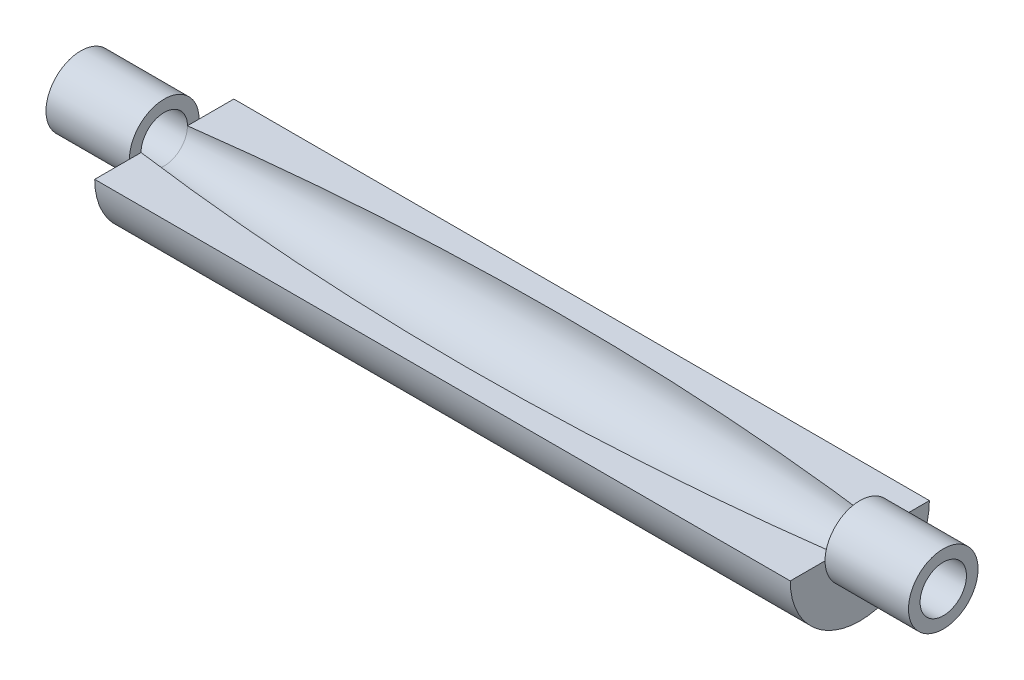
SolidWorks part; units mm, degrees
ref_plane "Front Plane" through (0, 0, 0) normal (0, 0, 1) x (1, 0, 0)
ref_plane "Top Plane" through (0, 0, 0) normal (0, 1, 0) x (1, 0, 0)
ref_plane "Right Plane" through (0, 0, 0) normal (1, 0, 0) x (0, 0, -1)
sketch "Sketch2" plane through (0, 0, 0) normal (0, 1, 0) x (1, 0, 0)
  line L0 (-186, -15) -> (-150, -15)
  line L1 (-150, -15) -> (-150, -30)
  line L2 (-150, -30) -> (150, -30)
  line L3 (150, -30) -> (150, -15)
  line L4 (150, -15) -> (186, -15)
  line L5 (186, -15) -> (186, -10)
  line L6 (186, -10) -> (150, -10)
  line L9 (-150, -10) -> (-186, -10)
  line L10 (-186, -10) -> (-186, -15)
  line L11 (-186, 0) -> (186, 0) construction
  arc A0 (-150, -10) -> (150, -10) centre (0, 1110) ccw
  point P16 (0, 0)
  point P17 (0, -20)
  dimension "D1" = 300
  dimension "D2" = 5
  dimension "D3" = 36
  dimension "D4" = 20
  dimension "D5" = 10
  dimension "D6" = 10
revolve "Revolve2" add sketch "Sketch2" angle 180 about L11
sketch "Sketch3" plane through (0, 0, 0) normal (0, 0, 1) x (1, 0, 0)
  line L0 (-186, 0) -> (186, 0) construction
  line L1 (-186, 10) -> (-186, 15)
  line L2 (-186, 15) -> (-150, 15)
  line L3 (-150, 15) -> (-150, 10)
  line L4 (-150, 10) -> (-186, 10)
  dimension "D1" = 5
  dimension "D2" = 10
revolve "Revolve3" add sketch "Sketch3" angle 360 about L0
mirror "Mirror1" about plane through (0, 0, 0) normal (1, 0, 0) of "Revolve3"
